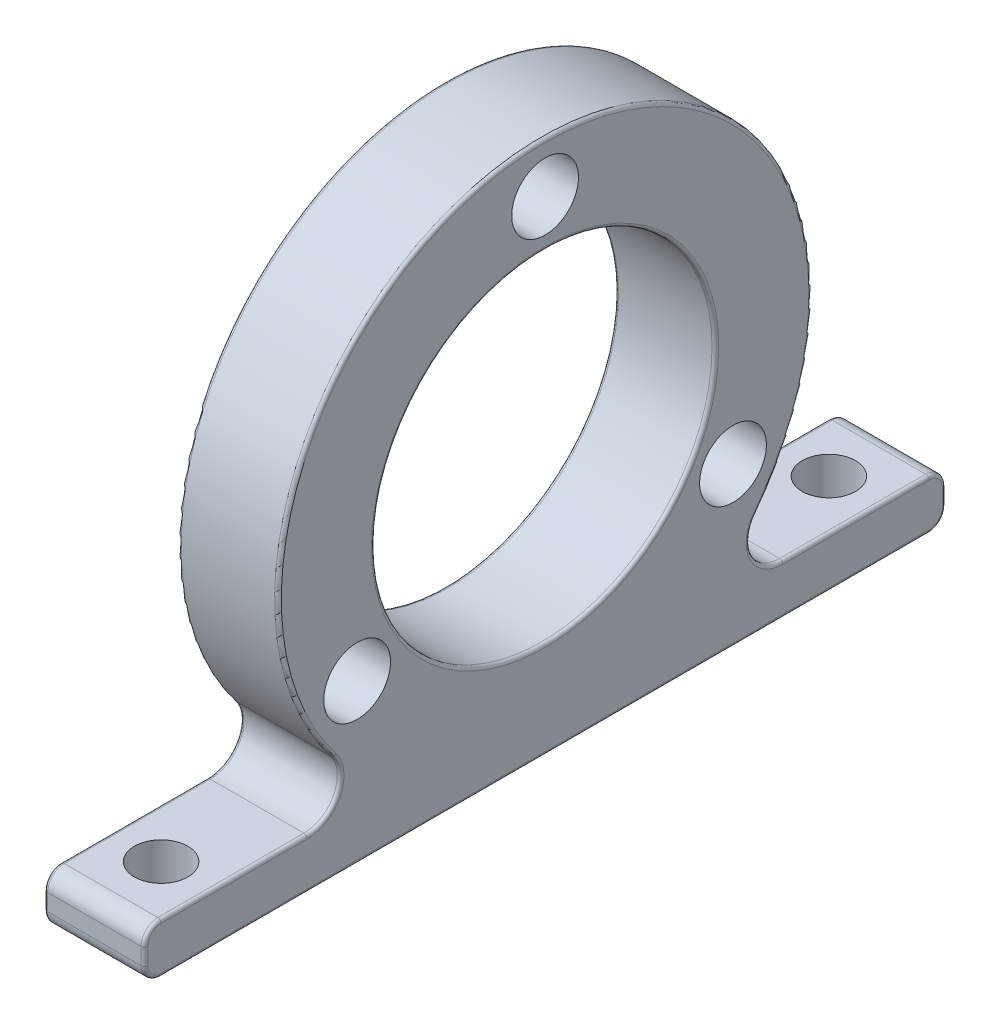
SolidWorks part; units mm, degrees
ref_plane "前视基准面" through (0, 0, 0) normal (0, 0, 1) x (1, 0, 0)
ref_plane "上视基准面" through (0, 0, 0) normal (0, 1, 0) x (1, 0, 0)
ref_plane "右视基准面" through (0, 0, 0) normal (1, 0, 0) x (0, 0, -1)
sketch "草图1" plane through (0, 0, 0) normal (1, 0, 0) x (0, 0, -1)
  line L0 (-11.5, -6.5) -> (-7.1239, -6.5)
  line L1 (-12, -7) -> (-12, -7.5)
  line L2 (12, -7) -> (12, -7.5)
  line L5 (-11.5, -8) -> (11.5, -8)
  line L6 (7.1239, -6.5) -> (11.5, -6.5)
  arc A0 (6.3324, -4.8889) -> (-6.3324, -4.8889) centre (0, 0) ccw
  arc A1 (12, -7.5) -> (11.5, -8) centre (11.5, -7.5) cw
  arc A2 (12, -7) -> (11.5, -6.5) centre (11.5, -7) ccw
  arc A3 (-11.5, -6.5) -> (-12, -7) centre (-11.5, -7) ccw
  arc A4 (-11.5, -8) -> (-12, -7.5) centre (-11.5, -7.5) cw
  arc A5 (6.3324, -4.8889) -> (7.1239, -6.5) centre (7.1239, -5.5) ccw
  arc A6 (-7.1239, -6.5) -> (-6.3324, -4.8889) centre (-7.1239, -5.5) ccw
  circle A9 centre (0, 0) radius 5.1
  point P14 (3.9686, -6.5)
  dimension "D1" = 1
  dimension "D2" = 0.5
  dimension "D9" = 8
extrude "凸台-拉伸1" add sketch "草图1" along normal blind 3
sketch "草图5" plane through (0, -6.5, 0) normal (0, 1, 0) x (1, 0, 0)
  circle A0 centre (1.5, -10) radius 0.8
  circle A1 centre (1.5, 10) radius 0.8
extrude "切除-拉伸2" cut sketch "草图5" against normal up to next
fillet "圆角1" radius 0.1 26 edges at (0, -6.5, 9.312) (0, -6.6464, 11.8536) (0, -7.25, 12) (0, -7.8536, 11.8536) (0, -8, 0) (0, -7.8536, -11.8536) (0, -7.25, -12) (0, -6.6464, -11.8536) (0, -6.5, -9.312) (0, 8, 0) (3, 8, 0) (3, -6.5, -9.312) (3, -6.6464, -11.8536) (3, -7.25, -12) (3, -7.8536, -11.8536) (3, -8, 0) (3, -7.8536, 11.8536) (3, -7.25, 12) (3, -6.6464, 11.8536) (3, -6.5, 9.312) (0, 0, -5.1) (3, 0, -5.1) (0, -5.941, 6.2264) (0, -5.941, -6.2264) (3, -5.941, 6.2264) (3, -5.941, -6.2264)
sketch "草图6" plane through (3, 0, 0) normal (1, 0, 0) x (0, 0, -1)
  circle A0 centre (0, 6.5) radius 1
  circle A1 centre (5.6292, -3.25) radius 1
  circle A2 centre (-5.6292, -3.25) radius 1
  point P8 (0, 0)
  dimension "D1" = 3
extrude "切除-拉伸3" cut sketch "草图6" against normal up to next
